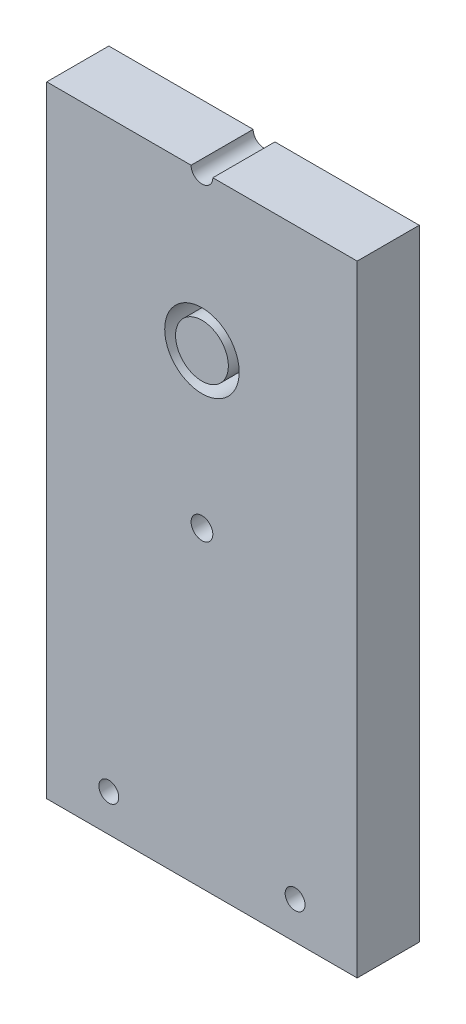
SolidWorks part; units mm, degrees
ref_plane "Front Plane" through (0, 0, 0) normal (0, 0, 1) x (1, 0, 0)
ref_plane "Top Plane" through (0, 0, 0) normal (0, 1, 0) x (1, 0, 0)
ref_plane "Right Plane" through (0, 0, 0) normal (1, 0, 0) x (0, 0, -1)
sketch "Sketch1" plane through (0, 0, 0) normal (0, 0, 1) x (1, 0, 0)
  line L1 (-25, 0) -> (25, 0)
  line L2 (-25, 0) -> (-25, 100)
  line L3 (-25, 100) -> (25, 100)
  line L4 (25, 0) -> (25, 100)
extrude "Boss-Extrude1" add sketch "Sketch1" along normal blind 10
sketch "Sketch2" plane through (0, 0, 0) normal (0, 0, 1) x (1, 0, 0)
  line L0 (25, 100) -> (-25, 100) construction
  circle A0 centre (0, 75) radius 4.25
  circle A1 centre (15, 6) radius 1.6
  circle A2 centre (-15, 6) radius 1.6
  circle A3 centre (0, 100) radius 1.75
  circle A4 centre (0, 50.25) radius 1.75
  circle A5 centre (0, 75) radius 6
extrude "Cut-Extrude2" cut sketch "Sketch2" along normal blind 11
